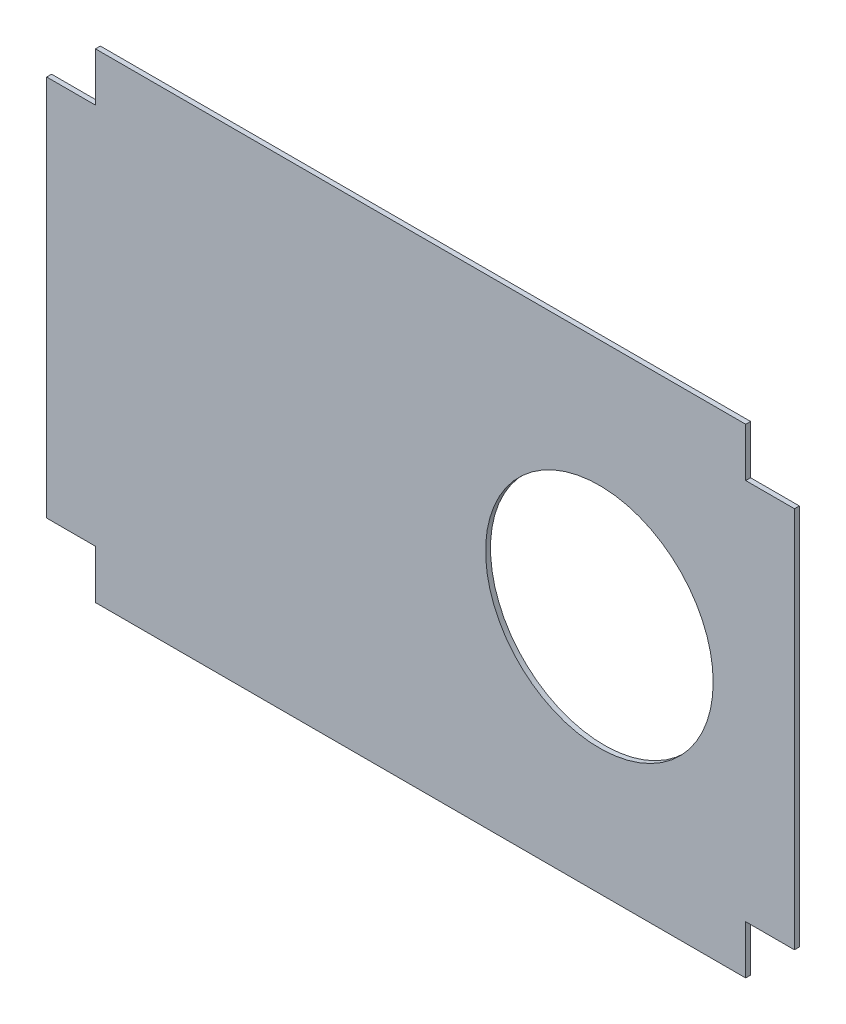
SolidWorks part; units mm, degrees
ref_plane "Přední rovina" through (0, 0, 0) normal (0, 0, 1) x (1, 0, 0)
ref_plane "Horní rovina" through (0, 0, 0) normal (0, 1, 0) x (1, 0, 0)
ref_plane "Pravá rovina" through (0, 0, 0) normal (1, 0, 0) x (0, 0, -1)
sketch "Skica1" plane through (0, 0, 0) normal (0, 0, 1) x (1, 0, 0)
  line L0 (-290.8164, 41.9962) -> (-290.8164, -193.0038)
  line L1 (-290.8164, 41.9962) -> (-260.8164, 41.9962)
  line L2 (-260.8164, 41.9962) -> (-260.8164, 71.9962)
  line L3 (-260.8164, 71.9962) -> (139.1836, 71.9962)
  line L4 (139.1836, 71.9962) -> (139.1836, 41.9962)
  line L5 (139.1836, 41.9962) -> (169.1836, 41.9962)
  line L6 (169.1836, -193.0038) -> (169.1836, 41.9962)
  line L8 (169.1836, -193.0038) -> (139.1836, -193.0038)
  line L9 (139.1836, -193.0038) -> (139.1836, -223.0038)
  line L10 (139.1836, -223.0038) -> (-260.8164, -223.0038)
  line L11 (-260.8164, -223.0038) -> (-260.8164, -193.0038)
  line L12 (-260.8164, -193.0038) -> (-290.8164, -193.0038)
  circle A0 centre (49.1836, -75.5038) radius 70
  dimension "D4" = 140
  dimension "D1" = 460
  dimension "D2" = 295
  dimension "D3" = 30
  dimension "D5" = 147.5
  dimension "D6" = 120
extrude "Přidat vysunutím1" add sketch "Skica1" along normal blind 3
